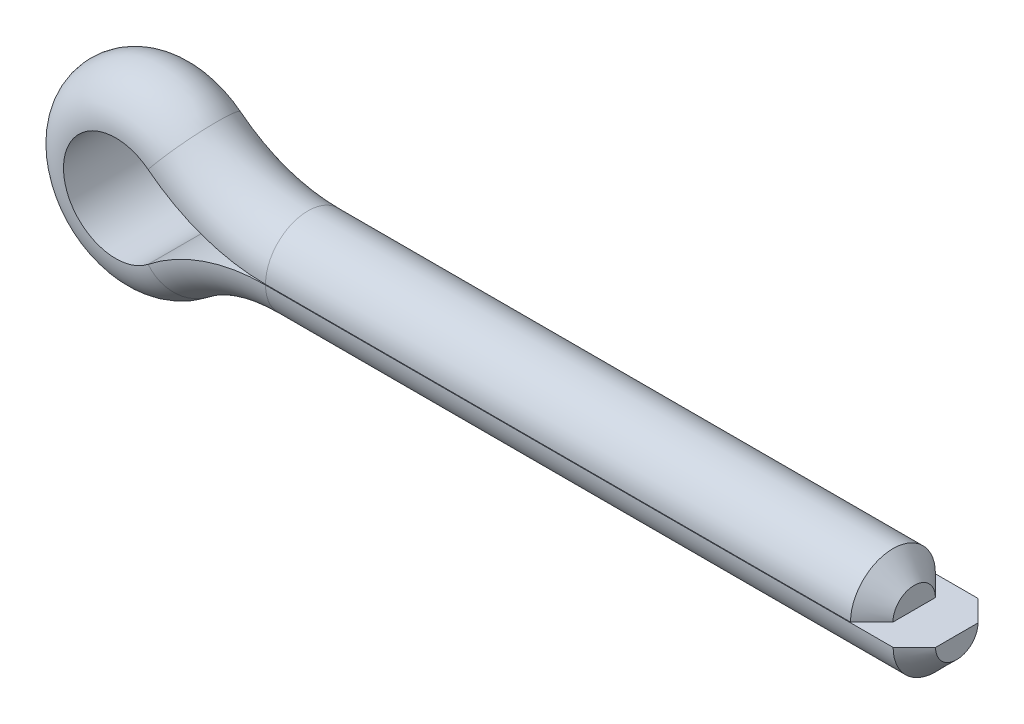
SolidWorks part; units mm, degrees
ref_plane "Front" through (0, 0, 0) normal (0, 0, 1) x (1, 0, 0)
ref_plane "Top" through (0, 0, 0) normal (0, 1, 0) x (1, 0, 0)
ref_plane "Right" through (0, 0, 0) normal (1, 0, 0) x (0, 0, -1)
sketch "Sketch1" plane through (0, 0, 0) normal (0, 0, 1) x (1, 0, 0)
  line L0 (-63.35, 0) -> (3.5719, 0) construction
  line L1 (-50.8, -0.0254) -> (3.5719, -0.0254)
  line L2 (-58.9686, 0.0254) -> (3.5719, 0.0254) construction
  line L3 (-50.8, 0.0254) -> (0, 0.0254)
  line L4 (-11.4985, 0.0254) -> (3.5719, 0.0254) construction
  line L5 (-11.4985, -0.0254) -> (3.5719, -0.0254) construction
  line L6 (-63.35, 4.3815) -> (-63.35, 0.8255) construction
  line L7 (-63.35, 4.3815) -> (-63.35, 7.9375) construction
  line L8 (-11.4985, 0) -> (3.5719, 0) construction
  line L9 (0, 0.0254) -> (0, 0) construction
  line L10 (-63.35, 0) -> (-63.35, -7.9375) construction
  arc A1 (-60.6354, 3.4393) -> (-60.6354, -3.4393) centre (-63.35, 0) ccw
  arc A2 (-50.8, -0.0254) -> (-60.6354, -3.4393) centre (-50.8, -15.9004) ccw
  arc A3 (-60.6354, 3.4393) -> (-50.8, 0.0254) centre (-50.8, 15.9004) ccw
  circle A4 centre (-63.35, 0) radius 7.9375 construction
  point P15 (0, 0.0254)
  dimension "D6" = 15.875
  dimension "D4" = 0.0254
  dimension "D5" = 0.0254
sketch "Sketch2" plane through (0, 0, 0) normal (1, 0, 0) x (0, 0, -1)
  line L0 (-3.556, 0.0254) -> (3.556, 0.0254)
  arc A0 (3.556, 0.0254) -> (-3.556, 0.0254) centre (0, 0.0254) ccw
sweep "Sweep1" add profiles "Sketch2" path "Sketch1"
chamfer "Chamfer1" distance 1.778 angle 45 2 edges at (3.5719, -3.5814, 0) (0, 3.5814, 0)
equation "\"D6@Sketch1\" = \"HeadOD@Sketch1\""
equation "\"WireWidth@Sketch2\" = \"WireWidth@Sketch1\""
equation "\"D1@Chamfer1\" = \"WireWidth@Sketch1\"*.25"
